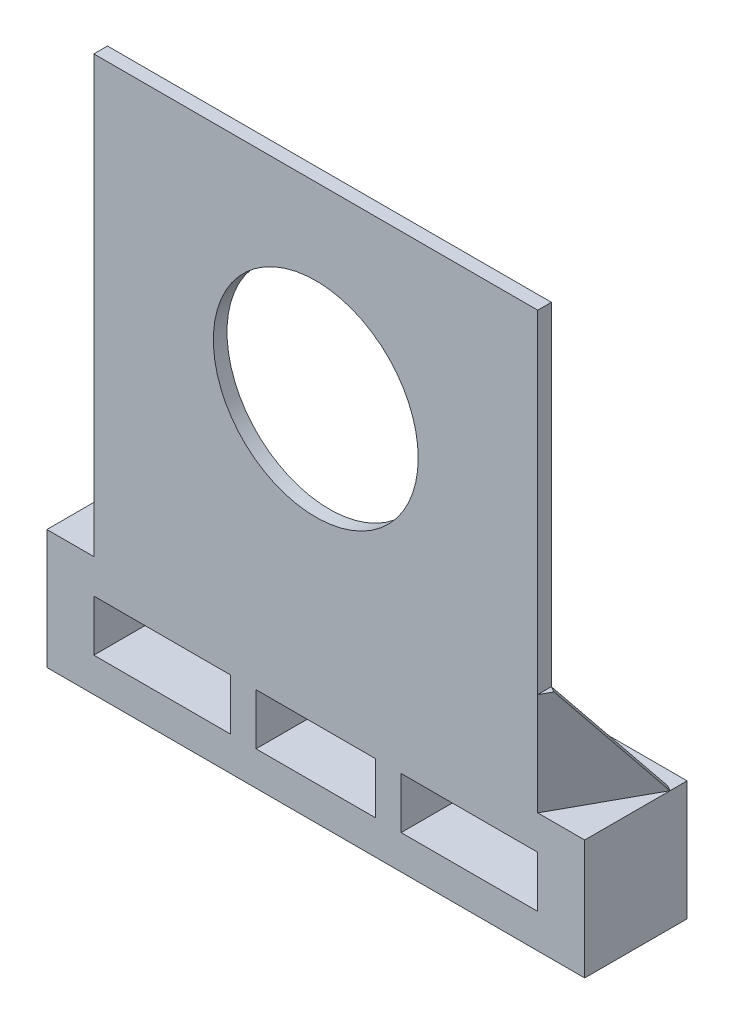
SolidWorks part; units mm, degrees
ref_plane "Front Plane" through (0, 0, 0) normal (0, 0, 1) x (1, 0, 0)
ref_plane "Top Plane" through (0, 0, 0) normal (0, 1, 0) x (1, 0, 0)
ref_plane "Right Plane" through (0, 0, 0) normal (1, 0, 0) x (0, 0, -1)
sketch "Sketch1" plane through (0, 0, 0) normal (0, 0, 1) x (1, 0, 0)
  line L1 (-130, 127.5) -> (130, 127.5)
  line L2 (-130, 127.5) -> (-130, -127.5)
  line L3 (-130, -127.5) -> (130, -127.5)
  line L4 (130, 127.5) -> (130, -127.5)
  line L5 (-130, 127.5) -> (130, -127.5) construction
  line L6 (-130, -127.5) -> (130, 127.5) construction
  circle A0 centre (0, 17.5) radius 60
  point P0 (0, 0)
  point P8 (0, 0)
  dimension "D3" = 120
  dimension "D1" = 255
  dimension "D2" = 260
  dimension "D4" = 110
extrude "Boss-Extrude1" add sketch "Sketch1" against normal blind 8
sketch "Sketch2" plane through (0, 0, 0) normal (0, 0, 1) x (1, 0, 0)
  line L0 (-130, -127.5) -> (130, -127.5) construction
  line L1 (-157.5, -127.5) -> (157.5, -127.5)
  line L2 (-157.5, -127.5) -> (-157.5, -197.5)
  line L3 (-157.5, -197.5) -> (157.5, -197.5)
  line L4 (157.5, -127.5) -> (157.5, -197.5)
  line L5 (-157.5, -127.5) -> (157.5, -197.5) construction
  line L6 (-157.5, -197.5) -> (157.5, -127.5) construction
  line L8 (-35, -147.5) -> (35, -147.5)
  line L9 (-35, -147.5) -> (-35, -177.5)
  line L10 (-35, -177.5) -> (35, -177.5)
  line L11 (35, -147.5) -> (35, -177.5)
  line L12 (-35, -147.5) -> (35, -177.5) construction
  line L13 (-35, -177.5) -> (35, -147.5) construction
  line L14 (50, -147.5) -> (130, -147.5)
  line L15 (50, -147.5) -> (50, -177.5)
  line L16 (50, -177.5) -> (130, -177.5)
  line L17 (130, -147.5) -> (130, -177.5)
  line L18 (50, -147.5) -> (130, -177.5) construction
  line L19 (50, -177.5) -> (130, -147.5) construction
  line L20 (-130, -147.5) -> (-50, -147.5)
  line L21 (-130, -147.5) -> (-130, -177.5)
  line L22 (-130, -177.5) -> (-50, -177.5)
  line L23 (-50, -147.5) -> (-50, -177.5)
  line L24 (-130, -147.5) -> (-50, -177.5) construction
  line L25 (-130, -177.5) -> (-50, -147.5) construction
  point P0 (0, -162.5)
  point P5 (90, -162.5)
  point P9 (0, -162.5)
  point P18 (-90, -162.5)
  point P23 (0, 0)
  point P24 (35, -162.5)
  dimension "D1" = 315
  dimension "D2" = 70
  dimension "D3" = 70
  dimension "D4" = 30
  dimension "D5" = 80
  dimension "D6" = 15
  dimension "D7" = 15
extrude "Boss-Extrude2" add sketch "Sketch2" against normal blind 60
sketch "Sketch3" plane through (0, -127.5, 0) normal (0, 1, 0) x (1, 0, 0)
  line L0 (130, 0) -> (157.5, 50)
  line L1 (157.5, 60) -> (157.5, 0) construction
  line L2 (130, 0) -> (130, 8)
  line L3 (130, 8) -> (154.1219, 51.858)
  line L4 (154.1219, 51.858) -> (157.5, 50)
  dimension "D1" = 50
extrude "Boss-Extrude3" add sketch "Sketch3" along normal blind 60
sketch "Sketch4" plane through (99.8081, 0, 54.8944) normal (0.8762, 0, 0.4819) x (0.4819, 0, -0.8762)
  line L0 (69.6592, -67.5) -> (119.713, -127.5)
  line L1 (119.713, -127.5) -> (119.713, -67.5)
  line L2 (119.713, -67.5) -> (69.6592, -67.5)
extrude "Cut-Extrude1" cut sketch "Sketch4" against normal through all
mirror "Mirror1" about plane through (0, 0, 0) normal (1, 0, 0) of "Cut-Extrude1", "Boss-Extrude3"
